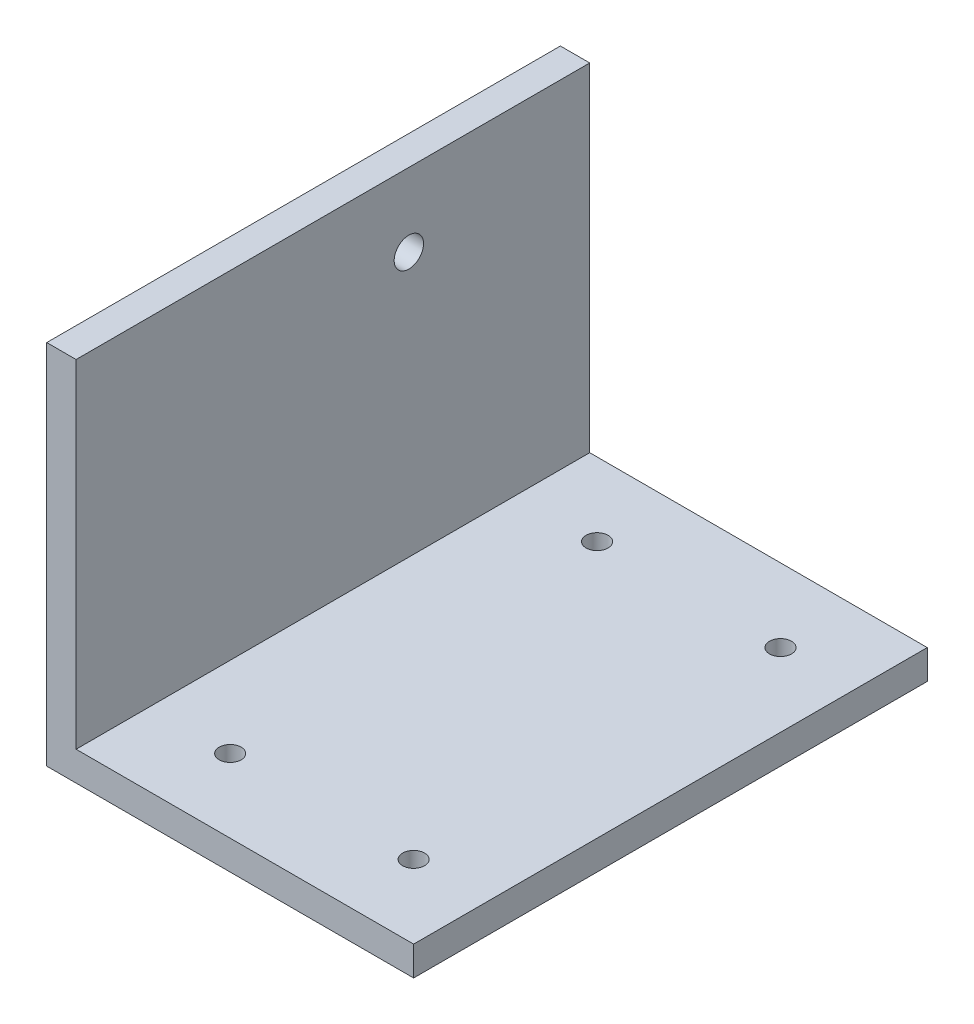
SolidWorks part; units mm, degrees
ref_plane "Plan de face" through (0, 0, 0) normal (0, 0, 1) x (1, 0, 0)
ref_plane "Plan de dessus" through (0, 0, 0) normal (0, 1, 0) x (1, 0, 0)
ref_plane "Plan de droite" through (0, 0, 0) normal (1, 0, 0) x (0, 0, -1)
sketch "Esquisse1" plane through (0, 0, 0) normal (0, 0, 1) x (1, 0, 0)
  line L1 (0, 0) -> (4, 0)
  line L2 (0, 0) -> (0, 50)
  line L3 (0, 50) -> (4, 50)
  line L4 (4, 4) -> (4, 50)
  line L5 (4, 0) -> (50, 0)
  line L7 (4, 4) -> (50, 4)
  line L8 (50, 0) -> (50, 4)
  dimension "D1" = 50
  dimension "D2" = 4
  dimension "D3" = 4
  dimension "D4" = 46
extrude "Extrusion1" add sketch "Esquisse1" along normal blind 70
sketch "Esquisse2" plane through (0, 4, 0) normal (0, 1, 0) x (1, 0, 0)
  line L0 (50, -70) -> (4, -70) construction
  line L1 (50, -70) -> (50, 0) construction
  circle A0 centre (40, -60) radius 1.5
  dimension "D1" = 3
  dimension "D2" = 10
  dimension "D3" = 10
extrude "Extrusion2" cut sketch "Esquisse2" against normal through all
pattern_linear "Répétition linéaire1" count 2 spacing 50 along (0, 0, -1) count 2 spacing 25 along (-1, 0, 0) of "Extrusion2"
sketch "Esquisse3" plane through (0, 0, 0) normal (-1, 0, 0) x (0, 0, 1)
  circle A0 centre (24.65, 40) radius 2
extrude "Enlèv. mat.-Extru.1" cut sketch "Esquisse3" against normal blind 10
